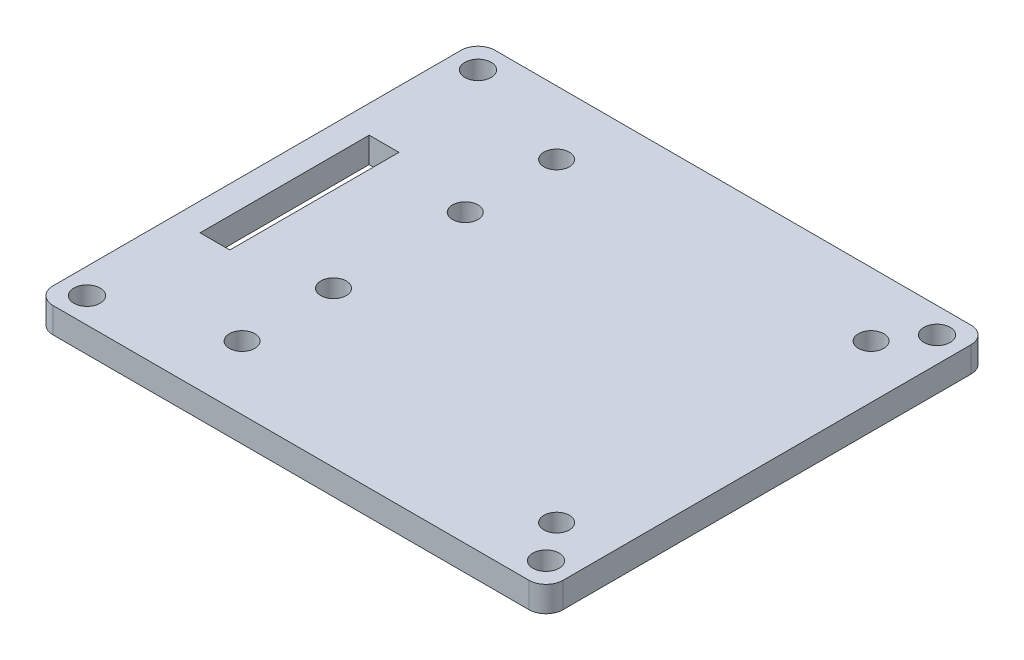
SolidWorks part; units mm, degrees
ref_plane "Front Plane" through (0, 0, 0) normal (0, 0, 1) x (1, 0, 0)
ref_plane "Top Plane" through (0, 0, 0) normal (0, 1, 0) x (1, 0, 0)
ref_plane "Right Plane" through (0, 0, 0) normal (1, 0, 0) x (0, 0, -1)
sketch "Sketch1" plane through (0, 0, 0) normal (0, 1, 0) x (1, 0, 0)
  line L0 (-18.5, 7.75) -> (-18.5, -7.75) construction
  line L1 (-21.5, -21.5) -> (21.5, -21.5) construction
  line L2 (-21.5, -21.5) -> (-21.5, 21.5) construction
  line L3 (-21.5, 21.5) -> (21.5, 21.5) construction
  line L4 (21.5, -21.5) -> (21.5, 21.5) construction
  line L5 (-18.5, -18.5) -> (18.5, -18.5) construction
  line L6 (-18.5, -18.5) -> (-18.5, 18.5) construction
  line L7 (-18.5, 18.5) -> (18.5, 18.5) construction
  line L8 (18.5, -18.5) -> (18.5, 18.5) construction
  line L9 (-16.5, 10.15) -> (-32, 10.15) construction
  line L10 (-16.5, 10.15) -> (-16.5, -10.15) construction
  line L11 (-16.5, -10.15) -> (-32, -10.15) construction
  line L12 (-32, 10.15) -> (-32, -10.15) construction
  line L13 (-32.25, 23) -> (21.75, 23) construction
  line L14 (-28.5, 9.95) -> (-32, 9.95)
  line L15 (-28.5, 9.95) -> (-28.5, -9.95)
  line L16 (-28.5, -9.95) -> (-32, -9.95)
  line L17 (-32, 9.95) -> (-32, -9.95)
  line L18 (-35.25, 26) -> (24.75, 26)
  line L19 (-35.25, 26) -> (-35.25, -26)
  line L20 (-35.25, -26) -> (24.75, -26)
  line L21 (24.75, 26) -> (24.75, -26)
  line L22 (21.75, 23) -> (21.75, -23) construction
  line L23 (-32.25, -23) -> (21.75, -23) construction
  line L24 (-32.25, 23) -> (-32.25, -23) construction
  circle A0 centre (-18.5, -18.5) radius 1.5
  circle A1 centre (-18.5, 18.5) radius 1.5
  circle A2 centre (18.5, 18.5) radius 1.5
  circle A3 centre (18.5, -18.5) radius 1.5
  circle A4 centre (-18.5, -7.75) radius 1.5
  circle A5 centre (-18.5, 7.75) radius 1.5
  circle A7 centre (-32.25, 23) radius 1.55
  circle A8 centre (21.75, 23) radius 1.55
  circle A9 centre (21.75, -23) radius 1.55
  circle A10 centre (-32.25, -23) radius 1.55
  point P4 (0, -18.5)
  point P9 (0, -21.5)
  point P10 (-18.5, 0)
  point P11 (-35.25, 0)
  point P12 (-21.5, 0)
  point P21 (-16.5, 0)
  point P26 (-18.5, 0)
  point P32 (0, 18.5)
  dimension "D5" = 3
  dimension "D6" = 3
  dimension "D7" = 3
  dimension "D8" = 3
  dimension "D11" = 3
  dimension "D12" = 3
  dimension "D22" = 3.1
  dimension "D23" = 3.1
  dimension "D24" = 3.1
  dimension "D25" = 3.1
  dimension "D1" = 43
  dimension "D2" = 43
  dimension "D3" = 37
  dimension "D4" = 37
  dimension "D9" = 20.3
  dimension "D10" = 15.5
  dimension "D13" = 15.5
  dimension "D14" = 0.2
  dimension "D15" = 0.2
  dimension "D16" = 3.5
  dimension "D17" = 2
  dimension "D18" = 52
  dimension "D19" = 60
  dimension "D20" = 3.25
  dimension "D21" = 3
extrude "Boss-Extrude1" add sketch "Sketch1" along normal blind 3
fillet "Fillet1" radius 2 4 edges at (-35.25, 1.5, -26) (-35.25, 1.5, 26) (24.75, 1.5, 26) (24.75, 1.5, -26)
